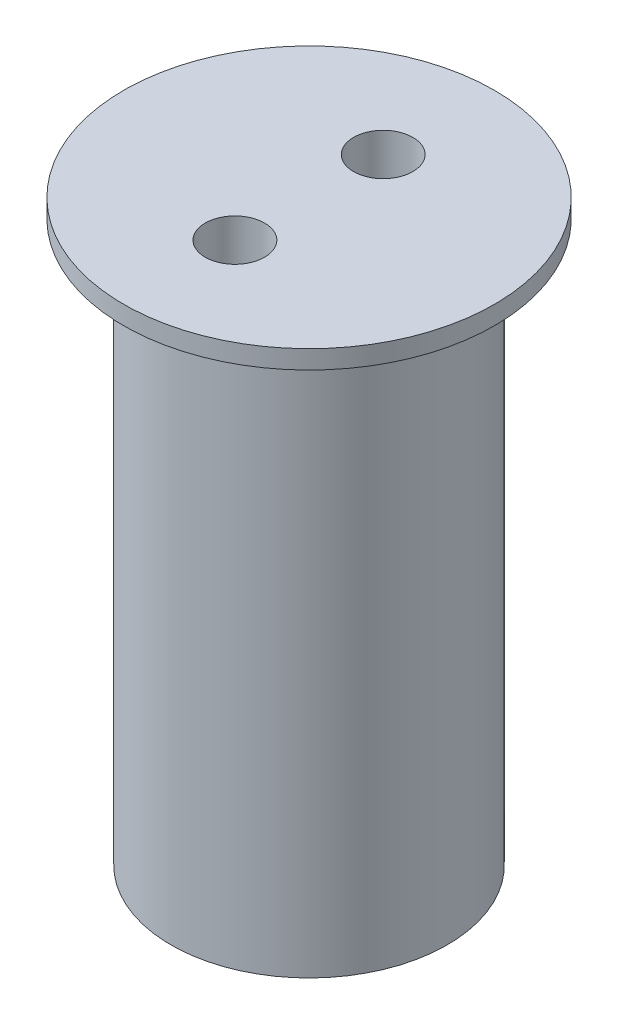
SolidWorks part; units mm, degrees
material "AISI 316 退火不锈钢条 (SS)"
ref_plane "前视基准面" through (0, 0, 0) normal (0, 0, 1) x (1, 0, 0)
ref_plane "上视基准面" through (0, 0, 0) normal (0, 1, 0) x (1, 0, 0)
ref_plane "右视基准面" through (0, 0, 0) normal (1, 0, 0) x (0, 0, -1)
other "Configuration Table"
sketch "草图1" plane through (0, 0, 0) normal (0, 0, 1) x (1, 0, 0)
  line L0 (0, 14.9695) -> (10, 14.9695)
  line L1 (10, 14.9695) -> (10, 13.9695)
  line L2 (10, 13.9695) -> (7.45, 13.9695)
  line L4 (7.45, -16.2305) -> (0, -16.2305)
  line L5 (0, -16.2305) -> (0, 14.9695)
  line L6 (7.45, 13.9695) -> (7.45, -16.2305)
  dimension "D2" = 31.2
  dimension "D3" = 10
  dimension "D4" = 1
revolve "旋转1" add sketch "草图1" angle 360 about L5
sketch "草图2" plane through (0, -16.2305, 0) normal (0, -1, 0) x (1, 0, 0)
  circle A0 centre (0, 0) radius 4 construction
  circle A1 centre (0, 4) radius 1.6
  circle A2 centre (0, -4) radius 1.6
extrude "切除-拉伸1" cut sketch "草图2" against normal blind 36
